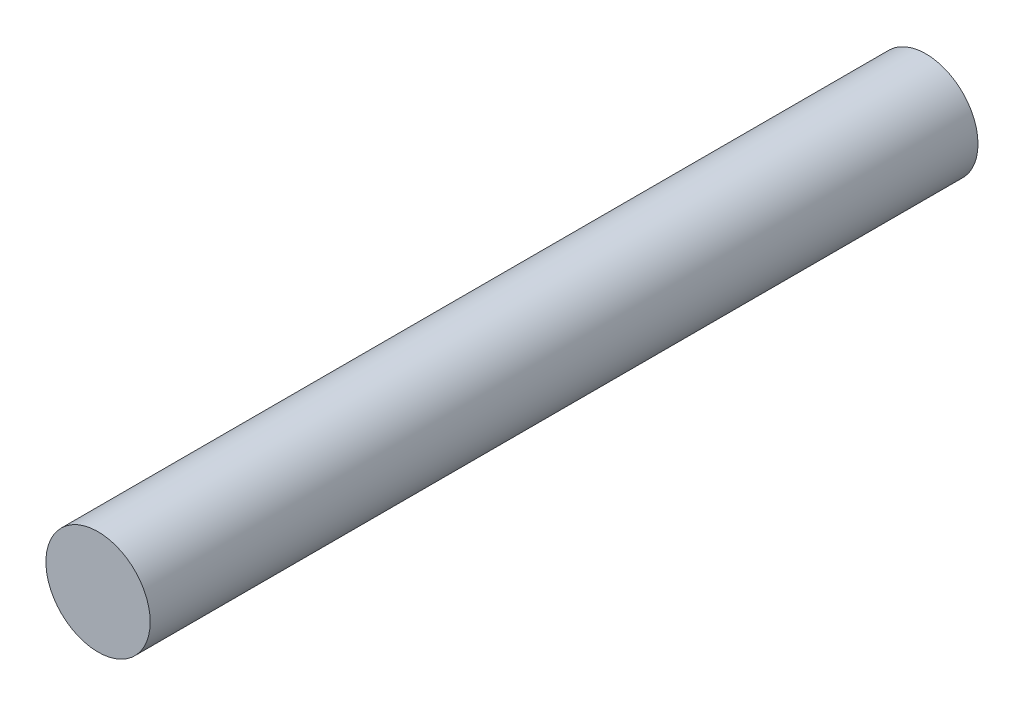
SolidWorks part; units mm, degrees
ref_plane "Front Plane" through (0, 0, 0) normal (0, 0, 1) x (1, 0, 0)
ref_plane "Top Plane" through (0, 0, 0) normal (0, 1, 0) x (1, 0, 0)
ref_plane "Right Plane" through (0, 0, 0) normal (1, 0, 0) x (0, 0, -1)
sketch "Sketch1" plane through (0, 0, 0) normal (0, 0, 1) x (1, 0, 0)
  circle A0 centre (0, 0) radius 2
  dimension "D1" = 4
extrude "Boss-Extrude1" add sketch "Sketch1" along normal blind 31.75
sketch "Sketch2" plane through (0, 0, 0) normal (0, 0, -1) x (-1, 0, 0)
  point P0 (0, 0)
